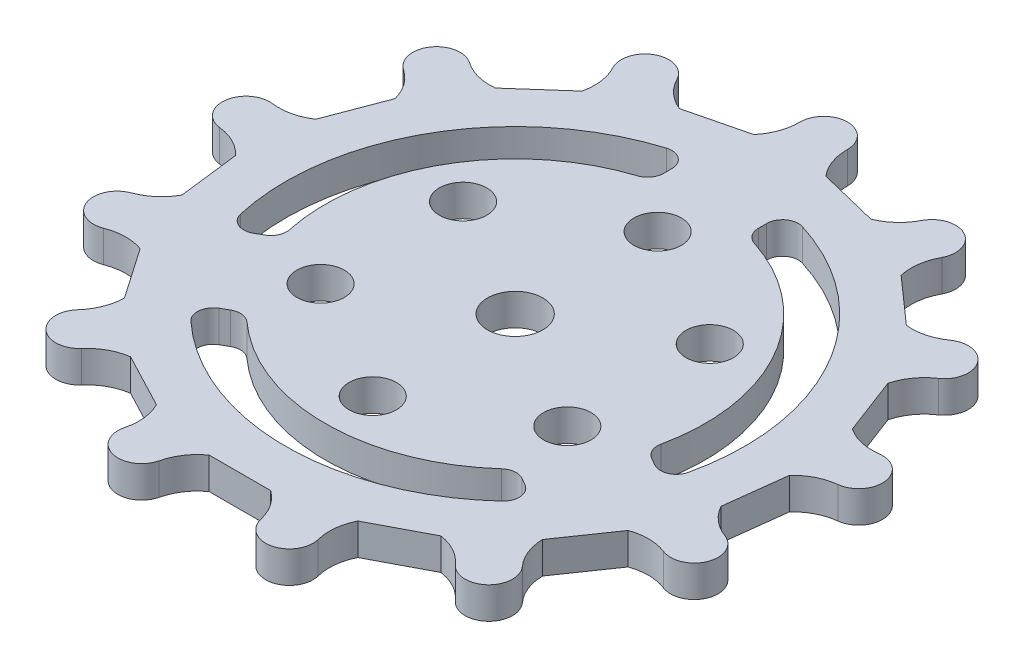
SolidWorks part; units mm, degrees
material "1060 Alloy"
ref_plane "Front Plane" through (0, 0, 0) normal (0, 0, 1) x (1, 0, 0)
ref_plane "Top Plane" through (0, 0, 0) normal (0, 1, 0) x (1, 0, 0)
ref_plane "Right Plane" through (0, 0, 0) normal (1, 0, 0) x (0, 0, -1)
sketch "Sketch1" plane through (0, 0, 0) normal (0, 1, 0) x (1, 0, 0)
  line L0 (0, 0) -> (9.2241, 0) construction
  line L1 (0, 0) -> (8.3653, 4.8297) construction
  line L2 (0, 22.5) -> (0, 19.5) construction
  line L3 (2.2759, 17.3514) -> (6.0484, 16.4216)
  line L4 (10.0788, 14.3062) -> (12.987, 11.7298)
  line L5 (15.5728, 7.9837) -> (16.9505, 4.3508)
  line L6 (17.4992, -0.1679) -> (17.0309, -4.0249)
  line L7 (15.4168, -8.2809) -> (13.2096, -11.4785)
  line L8 (9.8025, -14.4969) -> (6.3622, -16.3025)
  line L9 (1.9427, -17.3918) -> (-1.9427, -17.3918)
  line L10 (-6.3622, -16.3025) -> (-9.8025, -14.4969)
  line L11 (-13.2096, -11.4785) -> (-15.4168, -8.2809)
  line L12 (-17.0309, -4.0249) -> (-17.4992, -0.1679)
  line L13 (-16.9505, 4.3508) -> (-15.5728, 7.9837)
  line L14 (-12.987, 11.7298) -> (-10.0788, 14.3062)
  line L15 (-6.0484, 16.4216) -> (-2.2759, 17.3514)
  circle A0 centre (0, 0) radius 1.75
  circle A2 centre (0, 9) radius 1.5
  circle A3 centre (7.7942, -4.5) radius 1.5
  circle A4 centre (-7.7942, -4.5) radius 1.5
  circle A5 centre (7.7942, 4.5) radius 1.5
  circle A6 centre (0, -9) radius 1.5
  circle A7 centre (-7.7942, 4.5) radius 1.5
  arc A8 (1.4998, 19.4736) -> (-1.4998, 19.4736) centre (0, 19.5) ccw
  arc A9 (-1.5, 19.5) -> (-2.2759, 17.3514) centre (-4.7471, 19.4582) cw
  arc A10 (1.5, 19.5) -> (2.2759, 17.3514) centre (4.7471, 19.4582) ccw
  arc A11 (7.7339, 17.9635) -> (6.0484, 16.4216) centre (4.8393, 19.4355) cw
  arc A12 (10.3778, 16.546) -> (7.7218, 17.94) centre (9.0621, 17.2664) ccw
  arc A13 (10.3903, 16.5693) -> (10.0788, 14.3062) centre (13.246, 15.0233) ccw
  arc A14 (15.1961, 12.3117) -> (12.987, 11.7298) centre (13.3171, 14.9603) cw
  arc A15 (16.8784, 9.828) -> (15.1745, 12.2965) centre (16.0482, 11.0773) ccw
  arc A16 (16.9003, 9.8428) -> (15.5728, 7.9837) centre (18.7104, 7.1467) ccw
  arc A17 (19.177, 3.8395) -> (16.9505, 4.3508) centre (18.7441, 7.0579) cw
  arc A18 (19.5124, 0.8584) -> (19.1508, 3.8361) centre (19.3578, 2.3505) ccw
  arc A19 (19.5386, 0.8614) -> (17.4992, -0.1679) centre (19.8885, -2.3671) ccw
  arc A20 (18.7647, -5.5123) -> (17.0309, -4.0249) centre (19.8771, -2.4614) cw
  arc A21 (17.6763, -8.3077) -> (18.7399, -5.5031) centre (18.2328, -6.9148) ccw
  arc A22 (17.7009, -8.3173) -> (15.4168, -8.2809) centre (16.5104, -11.3386) ccw
  arc A23 (14.0537, -13.6013) -> (13.2096, -11.4785) centre (16.4564, -11.4168) cw
  arc A24 (11.7908, -15.5707) -> (14.036, -13.5817) centre (12.9309, -14.596) ccw
  arc A25 (11.8081, -15.5906) -> (9.8025, -14.4969) centre (9.3499, -17.7126) ccw
  arc A26 (6.1231, -18.5744) -> (6.3622, -16.3025) centre (9.2658, -17.7567) cw
  arc A27 (3.2041, -19.2666) -> (6.1165, -18.5488) centre (4.6667, -18.9334) ccw
  arc A28 (3.2102, -19.2923) -> (1.9427, -17.3918) centre (0.0475, -20.0288) ccw
  arc A29 (-3.2102, -19.2923) -> (-1.9427, -17.3918) centre (-0.0475, -20.0288) cw
  arc A30 (-6.1165, -18.5488) -> (-3.2041, -19.2666) centre (-4.6667, -18.9334) ccw
  arc A31 (-6.1231, -18.5744) -> (-6.3622, -16.3025) centre (-9.2658, -17.7567) ccw
  arc A32 (-11.8081, -15.5906) -> (-9.8025, -14.4969) centre (-9.3499, -17.7126) cw
  arc A33 (-14.036, -13.5817) -> (-11.7908, -15.5707) centre (-12.9309, -14.596) ccw
  arc A34 (-14.0537, -13.6013) -> (-13.2096, -11.4785) centre (-16.4564, -11.4168) ccw
  arc A35 (-17.7009, -8.3173) -> (-15.4168, -8.2809) centre (-16.5104, -11.3386) cw
  arc A36 (-18.7399, -5.5031) -> (-17.6763, -8.3077) centre (-18.2328, -6.9148) ccw
  arc A37 (-18.7647, -5.5123) -> (-17.0309, -4.0249) centre (-19.8771, -2.4614) ccw
  arc A38 (-19.5386, 0.8614) -> (-17.4992, -0.1679) centre (-19.8885, -2.3671) cw
  arc A39 (-19.1508, 3.8361) -> (-19.5124, 0.8584) centre (-19.3578, 2.3505) ccw
  arc A40 (-19.177, 3.8395) -> (-16.9505, 4.3508) centre (-18.7441, 7.0579) ccw
  arc A41 (-16.9003, 9.8428) -> (-15.5728, 7.9837) centre (-18.7104, 7.1467) cw
  arc A42 (-15.1745, 12.2965) -> (-16.8784, 9.828) centre (-16.0482, 11.0773) ccw
  arc A43 (-15.1961, 12.3117) -> (-12.987, 11.7298) centre (-13.3171, 14.9603) ccw
  arc A44 (-10.3903, 16.5693) -> (-10.0788, 14.3062) centre (-13.246, 15.0233) cw
  arc A45 (-7.7218, 17.94) -> (-10.3778, 16.546) centre (-9.0621, 17.2664) ccw
  arc A46 (-7.7339, 17.9635) -> (-6.0484, 16.4216) centre (-4.8393, 19.4355) ccw
  point P13 (0, 0)
  point P22 (0, 0)
  point P28 (0, 21)
  point P140 (0, 0)
  point P165 (0, 0)
  dimension "D1" = 3.5
  dimension "D2" = 13
  dimension "D3" = 3
  dimension "D4" = 9
  dimension "D7" = 3
  dimension "D8" = 9
  dimension "D10" = 3
  dimension "D11" = 19.5
  dimension "D12" = 13
  dimension "D6" = 30
  dimension "D5" = 3
  dimension "D9" = 3
extrude "Boss-Extrude3" add sketch "Sketch1" along normal blind 2 contours A46 A45 A44 L14 A43 A42 A41 L13 A40 A39 A38 L12 A37 A36 A35 L11 A34 A33 A32 L10 A31 A30 A29 L9 A28 A27 A26 L8 A25 A24 A23 L7 A22 A21 A20
sketch "Sketch3" plane through (0, 2, 0) normal (0, 1, 0) x (1, 0, 0)
  line L0 (-3, 14.1863) -> (-3, 11.619)
  line L1 (3, 14.1863) -> (3, 11.619)
  line L2 (13.7857, -4.4951) -> (11.5623, -3.2114)
  line L3 (10.7857, -9.6912) -> (8.5623, -8.4076)
  line L4 (-10.7857, -9.6912) -> (-8.5623, -8.4076)
  line L5 (-13.7857, -4.4951) -> (-11.5623, -3.2114)
  arc A0 (-3, 11.619) -> (-11.5623, -3.2114) centre (0, 0) ccw
  arc A1 (-3, 14.1863) -> (-13.7857, -4.4951) centre (0, 0) ccw
  circle A2 centre (0, 9) radius 1.5 construction
  arc A3 (-8.5623, -8.4076) -> (8.5623, -8.4076) centre (0, 0) ccw
  arc A4 (-10.7857, -9.6912) -> (10.7857, -9.6912) centre (0, 0) ccw
  arc A5 (11.5623, -3.2114) -> (3, 11.619) centre (0, 0) ccw
  arc A6 (13.7857, -4.4951) -> (3, 14.1863) centre (0, 0) ccw
  point P20 (0, 0)
  dimension "D1" = 24
  dimension "D2" = 29
  dimension "D3" = 3
  dimension "D4" = 3
  dimension "D5" = 3
extrude "Cut-Extrude1" cut sketch "Sketch3" against normal blind 2
fillet "Fillet1" radius 1 12 edges at (-13.7857, 1, 4.4951) (-10.7857, 1, 9.6912) (8.5623, 1, 8.4076) (-3, 1, -14.1863) (-8.5623, 1, 8.4076) (10.7857, 1, 9.6912) (-11.5623, 1, 3.2114) (-3, 1, -11.619) (13.7857, 1, 4.4951) (11.5623, 1, 3.2114) (3, 1, -11.619) (3, 1, -14.1863)
scale "Scale1" bodies to scale 104 scale about origin uniform scaling yes scale factor 2
